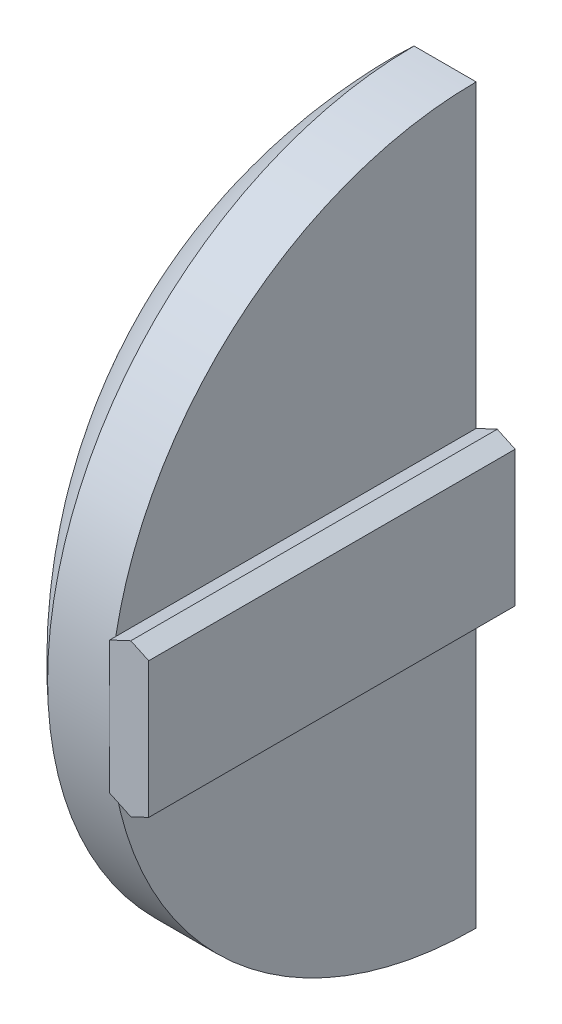
SolidWorks part; units mm, degrees
ref_plane "Front Plane" through (0, 0, 0) normal (0, 0, 1) x (1, 0, 0)
ref_plane "Top Plane" through (0, 0, 0) normal (0, 1, 0) x (1, 0, 0)
ref_plane "Right Plane" through (0, 0, 0) normal (1, 0, 0) x (0, 0, -1)
sketch "Sketch1" plane through (0, 0, 0) normal (0, 0, 1) x (1, 0, 0)
  line L0 (-22.49, 37.4977) -> (-20.79, 38.291) construction
  line L1 (-20.79, 38.291) -> (-19.3, 37.5957) construction
  line L2 (-19.3, 37.5957) -> (-19.3, 26.6084) construction
  line L3 (-19.3, 26.6084) -> (-20.79, 25.9131) construction
  line L4 (-20.79, 25.9131) -> (-22.49, 26.7064) construction
  line L5 (-22.49, 37.4425) -> (-20.79, 38.2359)
  line L6 (-20.79, 38.2359) -> (-19.35, 37.5639)
  line L7 (-19.35, 37.5639) -> (-19.35, 26.6403)
  line L8 (-19.35, 26.6403) -> (-20.79, 25.9683)
  line L9 (-20.79, 25.9683) -> (-22.49, 26.7616)
  line L10 (-22.4689, 37.4524) -> (-20.79, 38.2359) construction
  line L11 (-20.79, 25.9683) -> (-22.4689, 26.7518) construction
  line L12 (-22.49, 37.4425) -> (-22.49, 37.4977) construction
  line L13 (-22.49, 26.7064) -> (-22.49, 26.7616) construction
  line L14 (-22.49, 37.4425) -> (-22.49, 26.7616)
  dimension "D1" = 0.05
extrude "Boss-Extrude1" add sketch "Sketch1" against normal blind 29.5
sketch "Sketch2" plane through (0, 0, 0) normal (0, 0, 1) x (1, 0, 0)
  line L0 (-19.3, 32.1021) -> (-22.49, 32.1021) construction
  line L2 (-22.49, 37.4425) -> (-22.49, 26.7616) construction
ref_plane "Plane1" through (0, 32.1021, 0) normal (0, -1, 0) x (-1, 0, 0)
sketch "Sketch3" plane through (0, 32.1021, 0) normal (0, -1, 0) x (-1, 0, 0)
  line L0 (22.49, 29.5) -> (40.49, 29.5)
  line L1 (22.49, 0) -> (27.49, 0)
  line L2 (19.3, 0) -> (22.49, 0) construction
  line L3 (22.49, 29.5) -> (22.49, 0)
  line L4 (23.79, 28.2) -> (39.1711, 28.2)
  line L5 (23.79, 1.3) -> (26.9822, 1.3)
  line L6 (23.79, 28.2) -> (23.79, 1.3)
  arc A0 (40.49, 29.5) -> (27.49, 0) centre (0.7239, 29.4096) cw
  arc A1 (39.1711, 28.2) -> (26.9822, 1.3) centre (0.7239, 29.4096) cw
  dimension "D3" = 39.7662
  dimension "D1" = 18
  dimension "D2" = 5
  dimension "D4" = 1.3
revolve "Revolve1" add sketch "Sketch3" angle 360 about L0
sketch "Sketch4" plane through (0, 0, 0) normal (0, 1, 0) x (1, 0, 0)
  line L1 (-10.2812, 29.5) -> (-60.2812, 29.5)
  line L2 (-10.2812, 29.5) -> (-10.2812, 64.5)
  line L3 (-10.2812, 64.5) -> (-60.2812, 64.5)
  line L4 (-60.2812, 29.5) -> (-60.2812, 64.5)
  line L5 (-22.49, 0) -> (-22.49, 58.5126) construction
  dimension "D1" = 50
  dimension "D2" = 35
  dimension "D3" = 12.2088
  dimension "D4" = 29.5
extrude "Cut-Extrude1" cut sketch "Sketch4" along normal blind 68
sketch "Sketch5" plane through (0, 0, -29.5) normal (0, 0, -1) x (-1, 0, 0)
  line L1 (39.1711, 33.4021) -> (23.79, 33.4021)
  line L2 (39.1711, 33.4021) -> (39.1711, 30.8021)
  line L3 (39.1711, 30.8021) -> (23.79, 30.8021)
  line L4 (23.79, 33.4021) -> (23.79, 30.8021)
extrude "Cut-Extrude2" cut sketch "Sketch5" against normal blind 2
